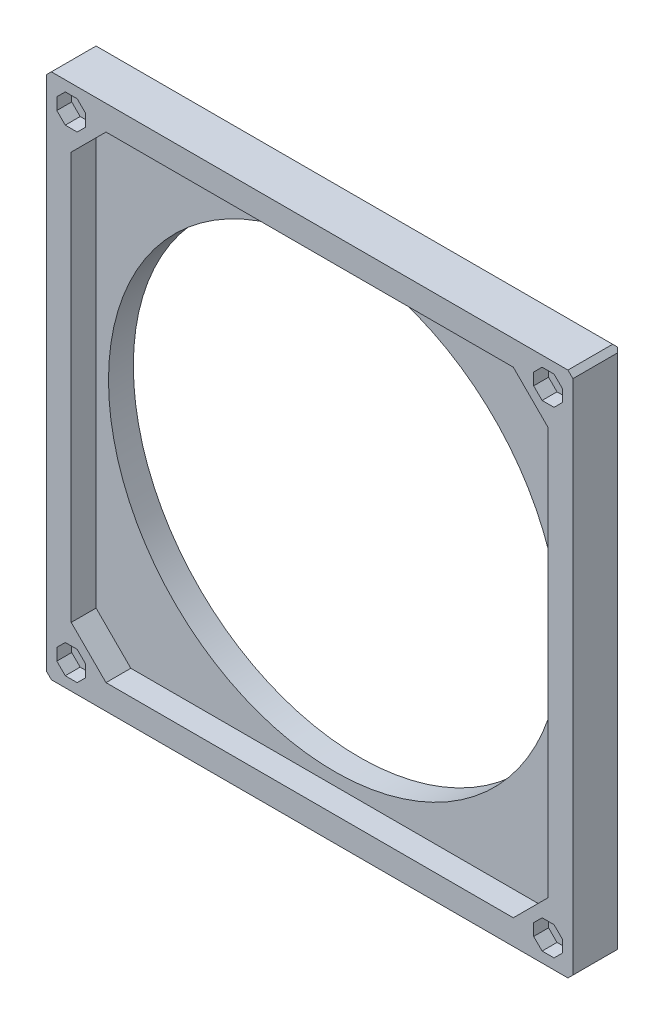
SolidWorks part; units mm, degrees
ref_plane "Front Plane" through (0, 0, 0) normal (0, 0, 1) x (1, 0, 0)
ref_plane "Top Plane" through (0, 0, 0) normal (0, 1, 0) x (1, 0, 0)
ref_plane "Right Plane" through (0, 0, 0) normal (1, 0, 0) x (0, 0, -1)
sketch "Sketch1 larger dia" plane through (0, 0, 0) normal (0, 0, 1) x (1, 0, 0)
  line L0 (-41, 48) -> (41, 48)
  line L1 (-53, 53) -> (53, 53)
  line L2 (-53, 53) -> (-53, -53)
  line L3 (-53, -53) -> (53, -53)
  line L4 (53, 53) -> (53, -53)
  line L5 (41, 48) -> (48, 41)
  line L6 (48, 41) -> (48, -41)
  line L7 (48, -41) -> (41, -48)
  line L8 (41, -48) -> (-41, -48)
  line L9 (-41, -48) -> (-48, -41)
  line L10 (-48, -41) -> (-48, 41)
  line L11 (-48, 41) -> (-41, 48)
  dimension "D2" = 12
  dimension "D3" = 5
  dimension "D4" = 5
  dimension "D5" = 5
  dimension "D6" = 5
  dimension "D8" = 12
  dimension "D9" = 12
  dimension "D10" = 12
  dimension "D11" = 12
  dimension "D12" = 12
sketch "Sketch3 holes" plane through (0, 0, 0) normal (0, 0, 1) x (1, 0, 0)
  line L1 (-53, 53) -> (53, 53) construction
  line L2 (-53, 53) -> (-53, -53) construction
  line L3 (-53, -53) -> (53, -53) construction
  line L4 (53, 53) -> (53, -53) construction
  circle A0 centre (-48, 48) radius 1.5
  circle A1 centre (48, 48) radius 1.5
  circle A2 centre (-48, -48) radius 1.5
  circle A3 centre (48, -48) radius 1.5
  dimension "D1" = 5
  dimension "D3" = 3
  dimension "D6" = 3
  dimension "D9" = 3
  dimension "D12" = 3
  dimension "D2" = 5
  dimension "D4" = 5
  dimension "D5" = 5
  dimension "D7" = 5
  dimension "D8" = 5
  dimension "D10" = 5
  dimension "D11" = 5
sketch "Sketch4 ring" plane through (0, 0, 0) normal (0, 0, 1) x (1, 0, 0)
  circle A0 centre (0, 0) radius 47.75
  circle A1 centre (0, 0) radius 45.5
  dimension "D1" = 95.5
  dimension "D2" = 91
extrude "Boss-Extrude1" add sketch "Sketch1 larger dia" along normal blind 5
sketch "Sketch5 smaller dia" plane through (0, 0, 0) normal (0, 0, -1) x (-1, 0, 0)
  line L1 (-53, 53) -> (53, 53)
  line L2 (-53, 53) -> (-53, -53)
  line L3 (-53, -53) -> (53, -53)
  line L4 (53, 53) -> (53, -53)
  circle A0 centre (0, 0) radius 45.5
  dimension "D1" = 91
extrude "Boss-Extrude2" add sketch "Sketch5 smaller dia" along normal blind 5
sketch "Sketch1" plane through (0, 0, 5) normal (0, 0, 1) x (1, 0, 0)
  line L0 (0, 53) -> (0, -53) construction
  line L1 (-53, 53) -> (53, 53) construction
  line L2 (-53, 53) -> (-53, -53) construction
  line L3 (-53, -53) -> (53, -53) construction
  line L4 (53, 53) -> (53, -53) construction
  line L5 (-45.1, 46.7988) -> (-45.1, 49.2012)
  line L6 (-45.1, 49.2012) -> (-46.7988, 50.9)
  line L7 (-46.7988, 50.9) -> (-49.2012, 50.9)
  line L8 (-49.2012, 50.9) -> (-50.9, 49.2012)
  line L9 (-50.9, 49.2012) -> (-50.9, 46.7988)
  line L10 (-50.9, 46.7988) -> (-49.2012, 45.1)
  line L11 (-49.2012, 45.1) -> (-46.7988, 45.1)
  line L12 (-46.7988, 45.1) -> (-45.1, 46.7988)
  line L13 (-53, 0) -> (53, 0) construction
  line L14 (-46.7988, -45.1) -> (-45.1, -46.7988)
  line L15 (-49.2012, -45.1) -> (-46.7988, -45.1)
  line L16 (-50.9, -46.7988) -> (-49.2012, -45.1)
  line L17 (-50.9, -49.2012) -> (-50.9, -46.7988)
  line L18 (-49.2012, -50.9) -> (-50.9, -49.2012)
  line L19 (-46.7988, -50.9) -> (-49.2012, -50.9)
  line L20 (-45.1, -49.2012) -> (-46.7988, -50.9)
  line L21 (-45.1, -46.7988) -> (-45.1, -49.2012)
  line L22 (46.7988, 45.1) -> (45.1, 46.7988)
  line L23 (49.2012, 45.1) -> (46.7988, 45.1)
  line L24 (50.9, 46.7988) -> (49.2012, 45.1)
  line L25 (50.9, 49.2012) -> (50.9, 46.7988)
  line L26 (49.2012, 50.9) -> (50.9, 49.2012)
  line L27 (46.7988, 50.9) -> (49.2012, 50.9)
  line L28 (45.1, 49.2012) -> (46.7988, 50.9)
  line L29 (45.1, 46.7988) -> (45.1, 49.2012)
  line L30 (45.1, -46.7988) -> (45.1, -49.2012)
  line L31 (45.1, -49.2012) -> (46.7988, -50.9)
  line L32 (46.7988, -50.9) -> (49.2012, -50.9)
  line L33 (49.2012, -50.9) -> (50.9, -49.2012)
  line L34 (50.9, -49.2012) -> (50.9, -46.7988)
  line L35 (50.9, -46.7988) -> (49.2012, -45.1)
  line L36 (49.2012, -45.1) -> (46.7988, -45.1)
  line L37 (46.7988, -45.1) -> (45.1, -46.7988)
  circle A4 centre (-48, 48) radius 2.9 construction
  circle A5 centre (-48, -48) radius 2.9 construction
  circle A6 centre (48, 48) radius 2.9 construction
  circle A7 centre (48, -48) radius 2.9 construction
  dimension "D3" = 5
  dimension "D13" = 5.8
  dimension "D2" = 5
  dimension "D4" = 106
extrude "Cut-Extrude1" cut sketch "Sketch1" against normal blind 3
chamfer "Chamfer2" distance 1 4 edges at (0, -53, -5) (53, 0, -5) (0, 53, -5) (-53, 0, -5)
chamfer "Chamfer3" distance 1 angle 45 4 edges at (53, -53, 0.5) (-53, -53, 0.5) (-53, 53, 0.5) (53, 53, 0.5)
